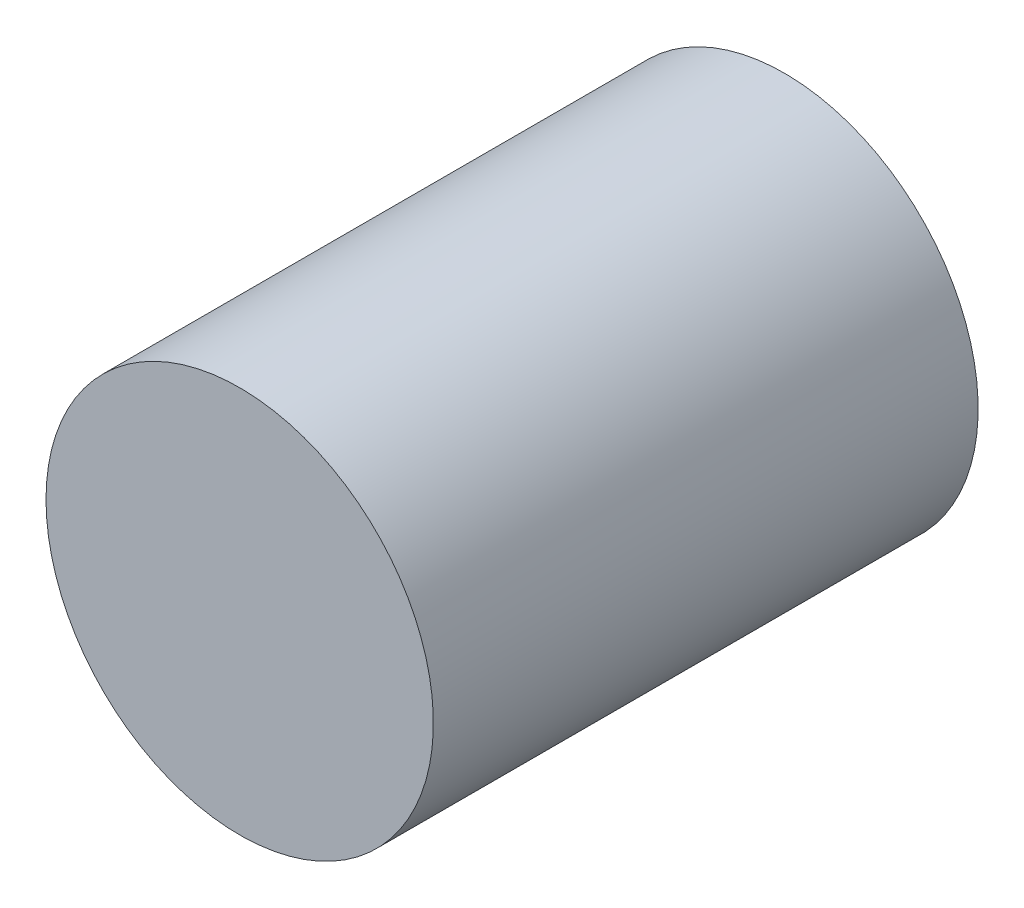
SolidWorks part; units mm, degrees
ref_plane "前视基准面" through (0, 0, 0) normal (0, 0, 1) x (1, 0, 0)
ref_plane "上视基准面" through (0, 0, 0) normal (0, 1, 0) x (1, 0, 0)
ref_plane "右视基准面" through (0, 0, 0) normal (1, 0, 0) x (0, 0, -1)
other "Configuration Table"
sketch "草图1" plane through (0, 0, 0) normal (0, 0, 1) x (1, 0, 0)
  circle A0 centre (0, 0) radius 16
  dimension "D1" = 32
extrude "凸台-拉伸1" add sketch "草图1" along normal blind 45
